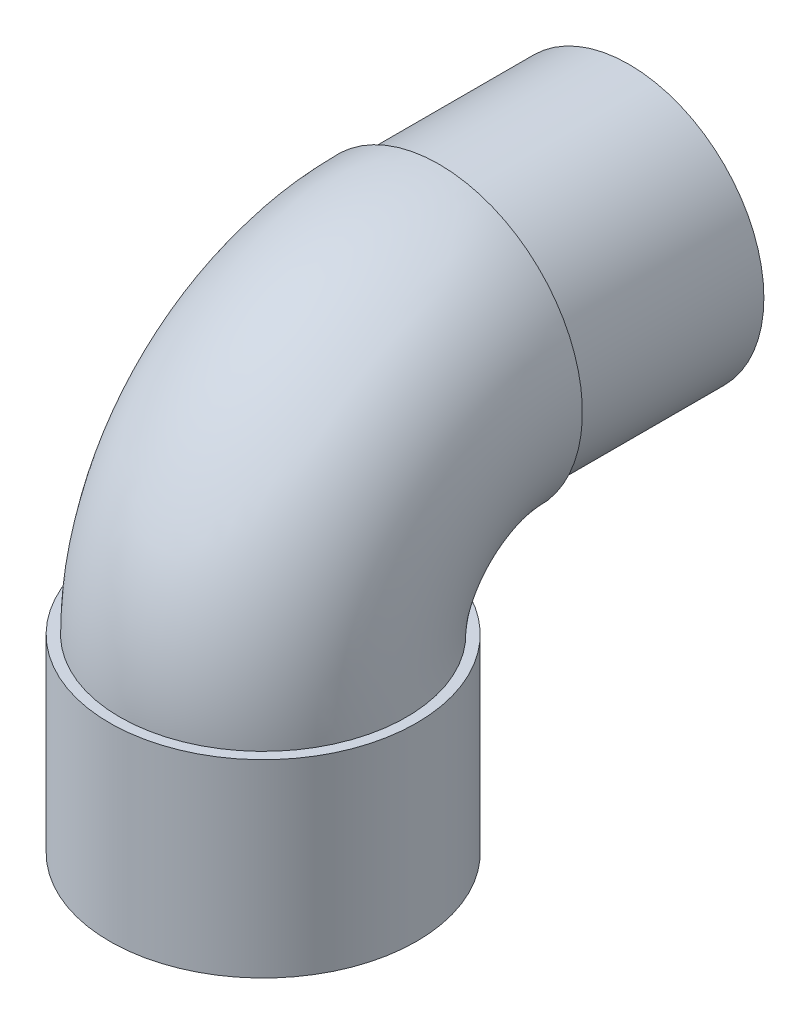
SolidWorks part; units mm, degrees
ref_plane "Plan de face" through (0, 0, 0) normal (0, 0, 1) x (1, 0, 0)
ref_plane "Plan de dessus" through (0, 0, 0) normal (0, 1, 0) x (1, 0, 0)
ref_plane "Plan de droite" through (0, 0, 0) normal (1, 0, 0) x (0, 0, -1)
sketch "Esquisse1" plane through (0, 0, 0) normal (0, 0, 1) x (1, 0, 0)
  line L0 (0, -20.7453) -> (41.9598, -20.7453)
  circle A0 centre (0, 0) radius 16.9
revolve "Révol.-Mince1" add sketch "Esquisse1" angle 90 about L0
sketch "Esquisse2" plane through (0, 0, 0) normal (0, 0, -1) x (-1, 0, 0)
  circle A0 centre (0, 0) radius 13.9
extrude "Extru.-Mince1" add sketch "Esquisse2" along normal blind 22.4 thin
sketch "Esquisse3" plane through (0, -20.7453, 0) normal (0, -1, 0) x (1, 0, 0)
  circle A0 centre (0, 20.7453) radius 16.1
extrude "Extru.-Mince2" add sketch "Esquisse3" along normal blind 22.3 thin
